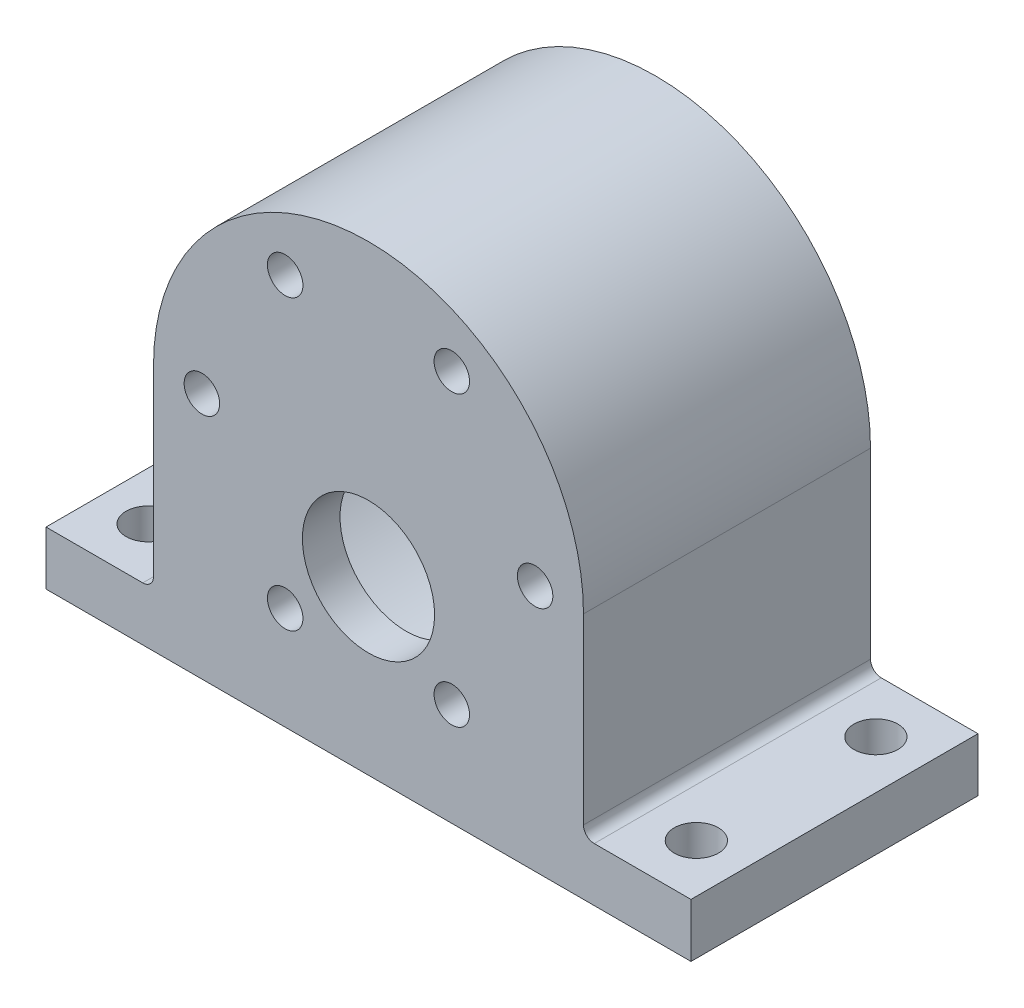
SolidWorks part; units mm, degrees
ref_plane "Plan de face" through (0, 0, 0) normal (0, 0, 1) x (1, 0, 0)
ref_plane "Plan de dessus" through (0, 0, 0) normal (0, 1, 0) x (1, 0, 0)
ref_plane "Plan de droite" through (0, 0, 0) normal (1, 0, 0) x (0, 0, -1)
sketch "Esquisse3" plane through (0, 0, 0) normal (0, 0, 1) x (1, 0, 0)
  line L0 (0, 0) -> (-20, 0) construction
  line L1 (0, 0) -> (78.5728, 0) construction
  line L2 (-20, 0) -> (-20, -17)
  line L3 (20, 0) -> (20, -17)
  line L4 (21, -18) -> (30, -18)
  line L5 (30, -18) -> (30, -23)
  line L6 (30, -23) -> (-30, -23)
  line L7 (-30, -23) -> (-30, -18)
  line L8 (-30, -18) -> (-21, -18)
  line L9 (0, -24.7843) -> (0, 28.7474) construction
  arc A0 (-20, 0) -> (20, 0) centre (0, 0) cw
  circle A1 centre (0, -7) radius 6.15
  circle A2 centre (-15.5, 0) radius 1.65
  circle A3 centre (-7.75, 13.4234) radius 1.65
  circle A4 centre (7.75, 13.4234) radius 1.65
  circle A5 centre (15.5, 0) radius 1.65
  circle A6 centre (7.75, -13.4234) radius 1.65
  circle A7 centre (-7.75, -13.4234) radius 1.65
  arc A8 (20, -17) -> (21, -18) centre (21, -17) ccw
  arc A9 (-20, -17) -> (-21, -18) centre (-21, -17) cw
  point P29 (0, 0)
  point P32 (-20, -18)
  dimension "D6" = 12.3
  dimension "D8" = 3.3
  dimension "D10" = 1
  dimension "D1" = 20
  dimension "D2" = 10
  dimension "D3" = 18
  dimension "D4" = 5
  dimension "D5" = 7
  dimension "D7" = 15.5
  dimension "D11" = 16
  dimension "D9" = 6
extrude "Boss.-Extru.2" add sketch "Esquisse3" against normal blind 3.5
sketch "Esquisse4" plane through (0, 0, -3.5) normal (0, 0, -1) x (-1, 0, 0)
  line L7 (-20, 0) -> (-20, -17)
  line L8 (-21, -18) -> (-30, -18)
  line L9 (-30, -18) -> (-30, -23)
  line L10 (-30, -23) -> (30, -23)
  line L11 (30, -23) -> (30, -18)
  line L12 (30, -18) -> (21, -18)
  line L13 (20, -17) -> (20, 0)
  line L14 (-20, 0) -> (-20, -17)
  line L15 (-21, -18) -> (-30, -18)
  line L16 (-30, -18) -> (-30, -23)
  line L17 (-30, -23) -> (30, -23)
  line L18 (30, -23) -> (30, -18)
  line L19 (30, -18) -> (21, -18)
  line L20 (20, -17) -> (20, 0)
  circle A0 centre (0, 0) radius 18.65
  arc A3 (20, 0) -> (-20, 0) centre (0, 0) ccw
  arc A4 (-21, -18) -> (-20, -17) centre (-21, -17) ccw
  arc A5 (20, -17) -> (21, -18) centre (21, -17) ccw
  arc A6 (20, 0) -> (-20, 0) centre (0, 0) ccw
  arc A7 (-21, -18) -> (-20, -17) centre (-21, -17) ccw
  arc A8 (20, -17) -> (21, -18) centre (21, -17) ccw
  dimension "D2" = 37.3
  dimension "D3" = 1.35
  dimension "D1" = 0
extrude "Boss.-Extru.3" add sketch "Esquisse4" along normal blind 23.2
sketch "Esquisse5" plane through (0, 0, 0) normal (0, 1, 0) x (1, 0, 0)
  line L0 (0, -4.6595) -> (0, 40.5567) construction
  line L1 (-25.5, 26.7) -> (-25.5, 0) construction
  line L2 (-32.1743, 13.35) -> (31.6447, 13.35) construction
  line L4 (-30, 0) -> (-21, 0)
  line L5 (-21, 0) -> (-21, 26.7)
  line L6 (-21, 26.7) -> (-30, 26.7)
  line L7 (-30, 26.7) -> (-30, 0)
  line L8 (-30, 0) -> (-21, 0)
  line L9 (-21, 0) -> (-21, 26.7)
  line L10 (-21, 26.7) -> (-30, 26.7)
  line L11 (-30, 26.7) -> (-30, 0)
  circle A0 centre (-25.5, 21.7) radius 2.05
  circle A1 centre (-25.5, 5) radius 2.05
  circle A2 centre (25.5, 5) radius 2.05
  circle A3 centre (25.5, 21.7) radius 2.05
  dimension "D2" = 4.1
  dimension "D3" = 5
  dimension "D4" = 51
  dimension "D5" = 5
  dimension "D6" = 16.7
  dimension "D1" = 0
extrude "Enlèv. mat.-Extru.1" cut sketch "Esquisse5" against normal blind 31 contours A0 | A1 | A3 | A2
